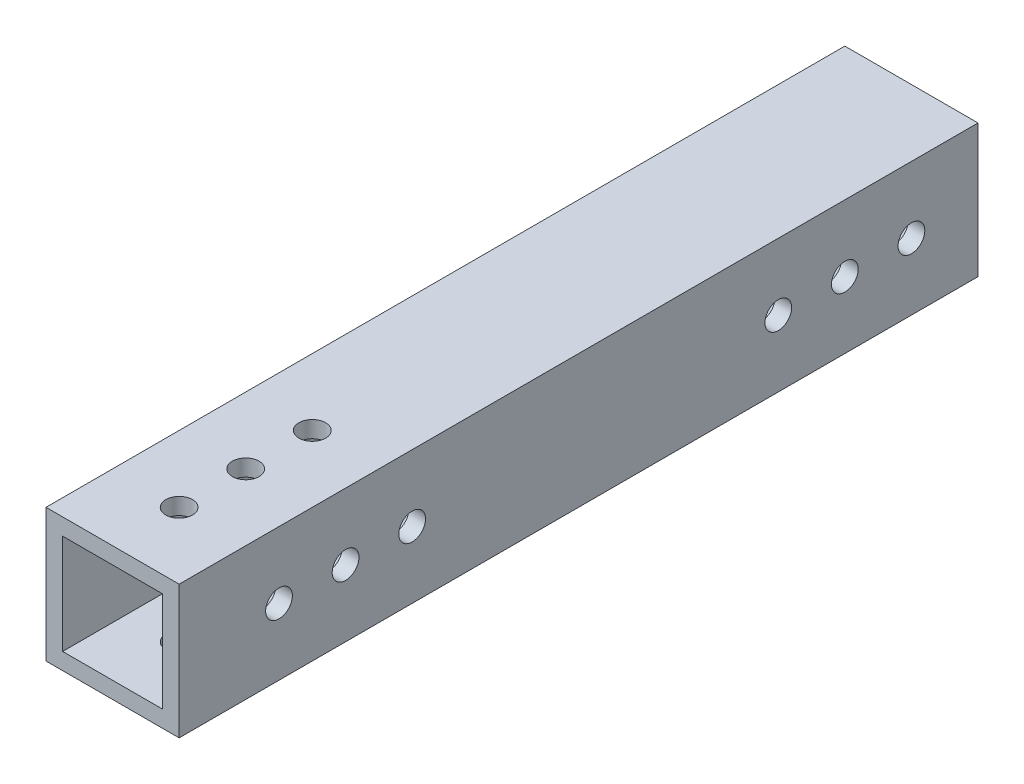
SolidWorks part; units mm, degrees
material "6061 Alloy"
ref_plane "Front" through (0, 0, 0) normal (0, 0, 1) x (1, 0, 0)
ref_plane "Top" through (0, 0, 0) normal (0, 1, 0) x (1, 0, 0)
ref_plane "Right" through (0, 0, 0) normal (1, 0, 0) x (0, 0, -1)
sketch "Sketch3" plane through (0, 0, 0) normal (0, 0, 1) x (1, 0, 0)
  line L1 (0, 0) -> (-25.4, 0)
  line L2 (0, 0) -> (0, 25.4)
  line L3 (0, 25.4) -> (-25.4, 25.4)
  line L4 (-25.4, 0) -> (-25.4, 25.4)
  line L5 (-3.175, 3.175) -> (-22.225, 3.175)
  line L6 (-3.175, 3.175) -> (-3.175, 22.225)
  line L7 (-3.175, 22.225) -> (-22.225, 22.225)
  line L8 (-22.225, 3.175) -> (-22.225, 22.225)
  dimension "D1" = 25.4
  dimension "D2" = 25.4
  dimension "D3" = 3.175
  dimension "D4" = 3.175
  dimension "D5" = 3.175
extrude "Boss-Extrude1" add sketch "Sketch3" along normal blind 152.4
hole_wizard "#10 Clearance Hole1" positions "Sketch4" profile "Sketch5" hole size "#10" standard "ANSI Inch"
sketch "Sketch4" plane through (0, 25.4, 0) normal (0, 1, 0) x (1, 0, 0)
  line L0 (0, -152.4) -> (-25.4, -152.4) construction
  line L1 (0, -152.4) -> (0, 0) construction
  point P0 (-12.7, -139.7)
  point P2 (-12.7, -127)
  point P4 (-12.7, -114.3)
  dimension "D1" = 12.7
  dimension "D2" = 12.7
  dimension "D3" = 12.7
  dimension "D4" = 12.7
sketch "Sketch5" plane through (-12.7, 25.4, 139.7) normal (1, 0, 0) x (0, 0, 1)
  line L0 (0, 0) -> (0, 26.9328)
  line L1 (0, 26.9328) -> (2.5527, 25.399)
  line L2 (2.5527, 25.399) -> (2.5527, 0)
  line L5 (2.5527, 0) -> (0, 0)
  line L10 (0, 26.9328) -> (-2.5527, 25.399) construction
  line L11 (0, -6.35) -> (0, 107.95) construction
  dimension "Hole Dia." = 5.1054
  dimension "Hole Depth" = 25.399
  dimension "Drill Angle" = 118
hole_wizard "#10 Clearance Hole2" positions "Sketch8" profile "Sketch7" hole size "#10" standard "ANSI Inch"
sketch "Sketch8" plane through (-25.4, 0, 0) normal (-1, 0, 0) x (0, 0, 1)
  line L0 (152.4, 25.4) -> (152.4, 0) construction
  line L1 (152.4, 25.4) -> (0, 25.4) construction
  point P0 (133.35, 12.7)
  point P2 (120.65, 12.7)
  point P4 (107.95, 12.7)
  dimension "D1" = 19.05
  dimension "D2" = 12.7
  dimension "D3" = 12.7
  dimension "D4" = 12.7
sketch "Sketch7" plane through (-25.4, 12.7, 133.35) normal (0, 1, 0) x (0, 0, 1)
  line L0 (0, 0) -> (0, 26.9328)
  line L1 (0, 26.9328) -> (2.5527, 25.399)
  line L2 (2.5527, 25.399) -> (2.5527, 0)
  line L5 (2.5527, 0) -> (0, 0)
  line L10 (0, 26.9328) -> (-2.5527, 25.399) construction
  line L11 (0, -6.35) -> (0, 107.95) construction
  dimension "Hole Dia." = 5.1054
  dimension "Hole Depth" = 25.399
  dimension "Drill Angle" = 118
hole_wizard "#10 Clearance Hole3" positions "Sketch9" profile "Sketch10" hole size "#10" standard "ANSI Inch"
sketch "Sketch9" plane through (0, 0, 0) normal (1, 0, 0) x (0, 0, -1)
  line L1 (0, 0) -> (0, 25.4) construction
  line L2 (-152.4, 25.4) -> (0, 25.4) construction
  point P0 (-12.7, 12.7)
  point P2 (-25.4, 12.7)
  point P4 (-38.1, 12.7)
  dimension "D1" = 12.7
  dimension "D2" = 12.7
  dimension "D3" = 12.7
  dimension "D4" = 12.7
sketch "Sketch10" plane through (0, 12.7, 12.7) normal (0, 1, 0) x (0, 0, -1)
  line L0 (0, 0) -> (0, 26.9328)
  line L1 (0, 26.9328) -> (2.5527, 25.399)
  line L2 (2.5527, 25.399) -> (2.5527, 0)
  line L5 (2.5527, 0) -> (0, 0)
  line L10 (0, 26.9328) -> (-2.5527, 25.399) construction
  line L11 (0, -6.35) -> (0, 107.95) construction
  dimension "Hole Dia." = 5.1054
  dimension "Hole Depth" = 25.399
  dimension "Drill Angle" = 118
